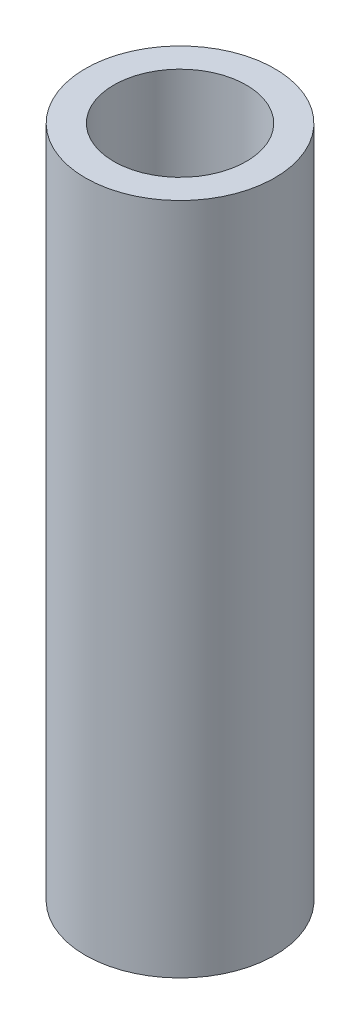
SolidWorks part; units mm, degrees
material "Custom Plastic"
ref_plane "X-Y Datum" through (0, 0, 0) normal (0, 0, 1) x (1, 0, 0)
ref_plane "X-Z Datum" through (0, 0, 0) normal (0, 1, 0) x (1, 0, 0)
ref_plane "Y-Z Datum" through (0, 0, 0) normal (1, 0, 0) x (0, 0, -1)
sketch "Sketch1" plane through (0, 0, 0) normal (0, 1, 0) x (1, 0, 0)
  circle A0 centre (0, 0) radius 2
  circle A1 centre (0, 0) radius 2.8575
  dimension "D1" = 4
  dimension "D2" = 5.715
extrude "Boss-Extrude1" add sketch "Sketch1" against normal blind 20.32
